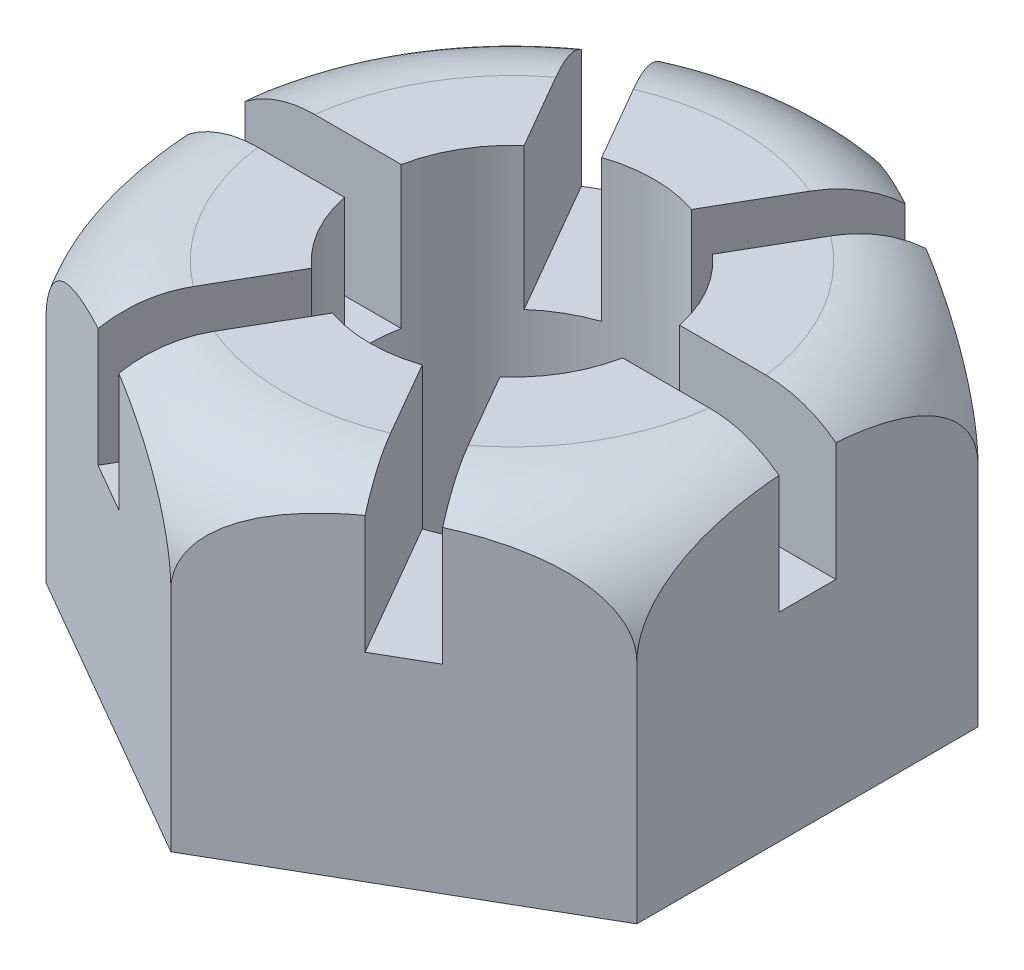
SolidWorks part; units mm, degrees
ref_plane "Front Plane" through (0, 0, 0) normal (0, 0, 1) x (1, 0, 0)
ref_plane "Top Plane" through (0, 0, 0) normal (0, 1, 0) x (1, 0, 0)
ref_plane "Right Plane" through (0, 0, 0) normal (1, 0, 0) x (0, 0, -1)
sketch "Sketch1" plane through (0, 0, 0) normal (0, 1, 0) x (1, 0, 0)
  line L1 (0, 15.2513) -> (-13.208, 7.6256)
  line L2 (-13.208, 7.6256) -> (-13.208, -7.6256)
  line L3 (-13.208, -7.6256) -> (0, -15.2513)
  line L4 (0, -15.2513) -> (13.208, -7.6256)
  line L5 (13.208, -7.6256) -> (13.208, 7.6256)
  line L6 (13.208, 7.6256) -> (0, 15.2513)
  circle A0 centre (0, 0) radius 13.208 construction
  dimension "D1" = 26.416
extrude "Boss-Extrude1" add sketch "Sketch1" along normal blind 15.24
sketch "Sketch2" plane through (0, 0, 0) normal (1, 0, 0) x (0, 0, -1)
  line L0 (15.2513, 15.24) -> (15.2513, 0) construction
  line L1 (7.6256, 15.24) -> (15.2513, 15.24) construction
  line L2 (15.2513, 10.16) -> (15.2513, 0)
  line L3 (7.6256, 15.24) -> (10.1713, 15.24)
  line L4 (7.6256, 15.24) -> (7.6256, 19.0047)
  line L5 (7.6256, 19.0047) -> (20.6071, 19.0047)
  line L6 (20.6071, 19.0047) -> (20.6071, 0)
  line L7 (20.6071, 0) -> (15.2513, 0)
  line L8 (0, 0) -> (0, 10.9807) construction
  arc A0 (15.2513, 10.16) -> (10.1713, 15.24) centre (10.1713, 10.16) ccw
  dimension "D1" = 5.08
revolve "Cut-Revolve2" cut sketch "Sketch2" angle 360 about L8
sketch "Sketch4" plane through (0, 15.24, 0) normal (0, 1, 0) x (1, 0, 0)
  line L0 (-7.7039, 10.8035) -> (-2.1997, 1.27)
  line L1 (0, 15.2513) -> (-13.208, 7.6256) construction
  line L2 (0, -15.2513) -> (13.208, -7.6256) construction
  line L3 (-5.5041, 12.0735) -> (0, 2.54)
  line L4 (-7.7039, 10.8035) -> (-5.5041, 12.0735)
  line L5 (5.5041, -12.0735) -> (7.7039, -10.8035)
  line L6 (13.208, 1.27) -> (2.1997, 1.27)
  line L7 (13.208, -1.27) -> (2.1997, -1.27)
  line L8 (13.208, 1.27) -> (13.208, -1.27)
  line L9 (-13.208, 1.27) -> (-13.208, -1.27)
  line L10 (-5.5041, -12.0735) -> (0, -2.54)
  line L11 (-7.7039, -10.8035) -> (-2.1997, -1.27)
  line L12 (-5.5041, -12.0735) -> (-7.7039, -10.8035)
  line L13 (7.7039, 10.8035) -> (5.5041, 12.0735)
  line L14 (2.1997, 1.27) -> (7.7039, 10.8035)
  line L16 (2.1997, -1.27) -> (7.7039, -10.8035)
  line L17 (0, 2.54) -> (5.5041, 12.0735)
  line L18 (-2.1997, 1.27) -> (-13.208, 1.27)
  line L21 (-2.1997, -1.27) -> (-13.208, -1.27)
  line L22 (0, -2.54) -> (5.5041, -12.0735)
  point P19 (0, 0)
  dimension "D1" = 1.27
  dimension "D2" = 1.27
  dimension "D3" = 3
extrude "Cut-Extrude2" cut sketch "Sketch4" against normal blind 6.35
sketch "Sketch8" plane through (0, 15.24, 0) normal (0, 1, 0) x (1, 0, 0)
  circle A0 centre (0, 0) radius 6.35
  dimension "D1" = 12.7
extrude "Cut-Extrude4" cut sketch "Sketch8" against normal through all
